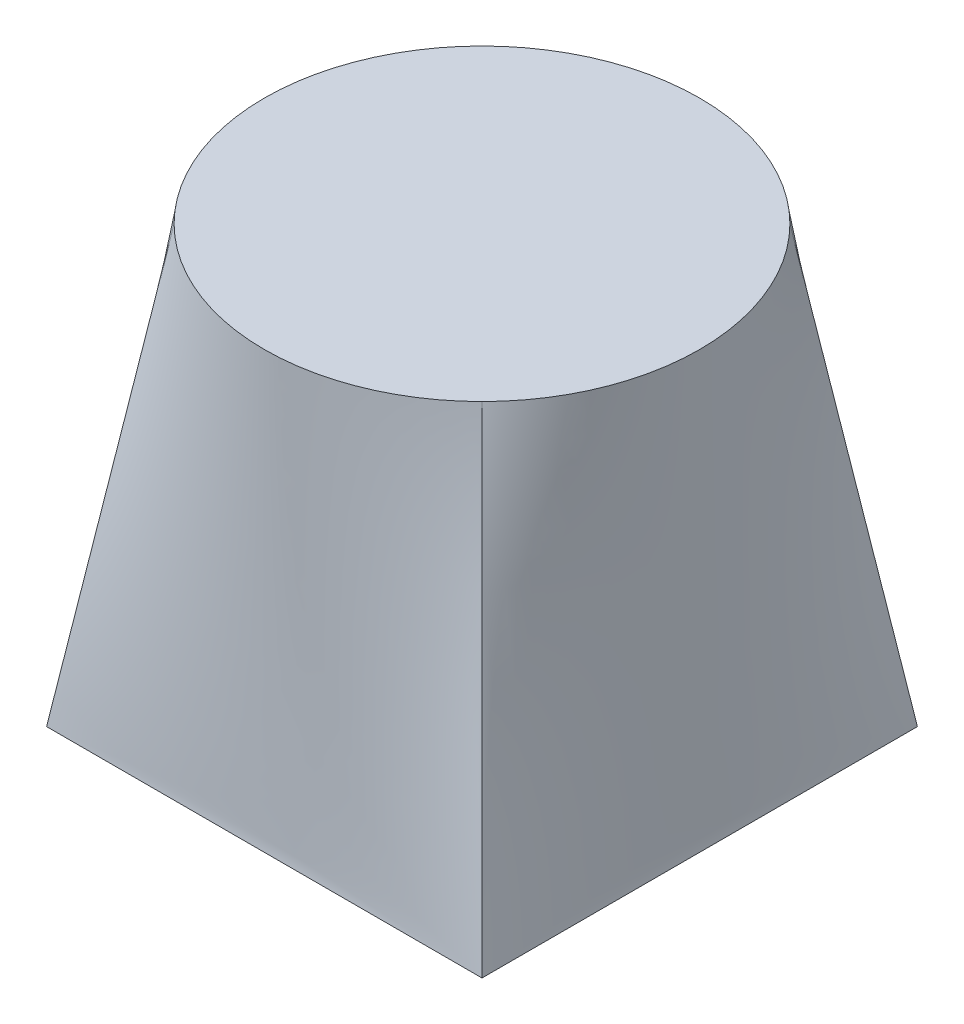
SolidWorks part; units mm, degrees
ref_plane "Front Plane" through (0, 0, 0) normal (0, 0, 1) x (1, 0, 0)
ref_plane "Top Plane" through (0, 0, 0) normal (0, 1, 0) x (1, 0, 0)
ref_plane "Right Plane" through (0, 0, 0) normal (1, 0, 0) x (0, 0, -1)
sketch "Sketch1" plane through (0, 0, 0) normal (0, 1, 0) x (1, 0, 0)
  line L1 (-5, -5) -> (5, -5)
  line L2 (-5, -5) -> (-5, 5)
  line L3 (-5, 5) -> (5, 5)
  line L4 (5, -5) -> (5, 5)
  line L5 (-5, -5) -> (5, 5) construction
  line L6 (-5, 5) -> (5, -5) construction
ref_plane "Plane1" through (0, 10, 0) normal (0, 1, 0) x (-1, 0, 0)
sketch "Sketch2" plane through (0, 10, 0) normal (0, 1, 0) x (-1, 0, 0)
  circle A0 centre (0, 0) radius 5
loft "Loft1" add profiles "Sketch1", "Sketch2"
